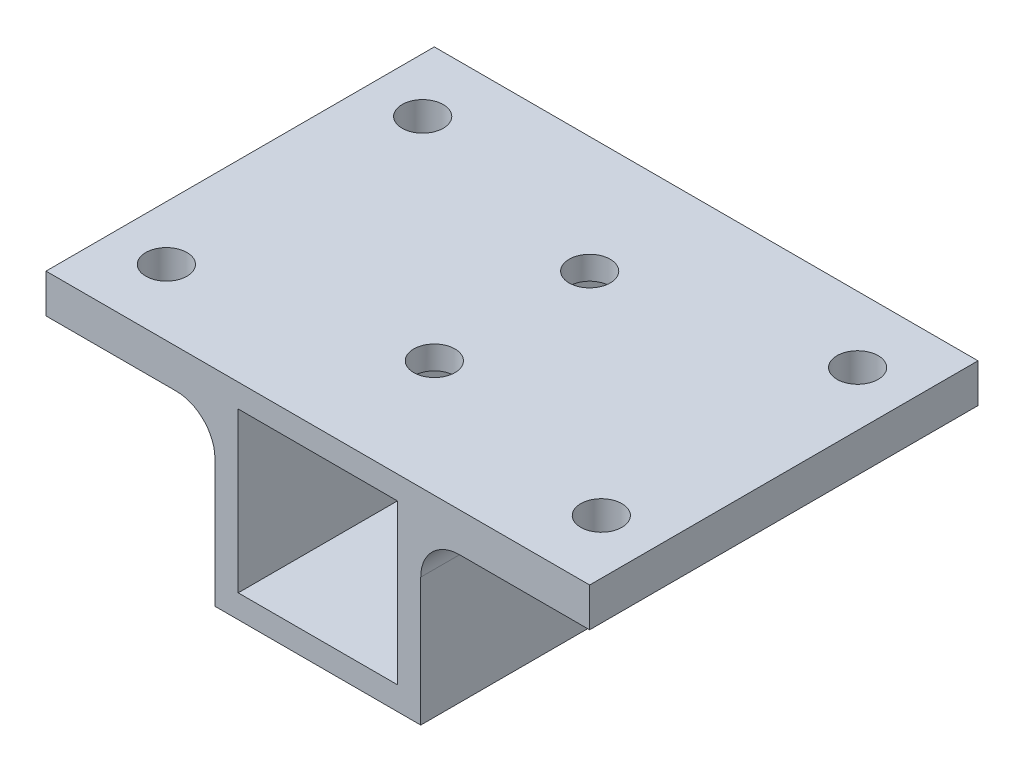
SolidWorks part; units mm, degrees
ref_plane "前视基准面" through (0, 0, 0) normal (0, 0, 1) x (1, 0, 0)
ref_plane "上视基准面" through (0, 0, 0) normal (0, 1, 0) x (1, 0, 0)
ref_plane "右视基准面" through (0, 0, 0) normal (1, 0, 0) x (0, 0, -1)
other "Configuration Table"
sketch "草图1" plane through (0, 0, 0) normal (0, 0, 1) x (1, 0, 0)
  line L0 (-13.25, 13.25) -> (13.25, 13.25)
  line L1 (-10.25, -10.25) -> (10.25, -10.25)
  line L2 (-10.25, -10.25) -> (-10.25, 10.25)
  line L3 (-10.25, 10.25) -> (10.25, 10.25)
  line L4 (10.25, -10.25) -> (10.25, 10.25)
  line L5 (-10.25, -10.25) -> (10.25, 10.25) construction
  line L6 (-10.25, 10.25) -> (10.25, -10.25) construction
  line L7 (13.25, -13.25) -> (13.25, 13.25)
  line L8 (-13.25, -13.25) -> (13.25, -13.25)
  line L9 (-13.25, -13.25) -> (-13.25, 13.25)
  point P0 (0, 0)
  dimension "D1" = 20.5
  dimension "D2" = 20.5
  dimension "D3" = 3
extrude "凸台-拉伸3" add sketch "草图1" along normal blind 50
sketch "草图2" plane through (0, 13.25, 0) normal (0, 1, 0) x (1, 0, 0)
  line L0 (-1013.25, -25) -> (48986.75, -25) construction
  line L1 (-13.25, -50) -> (-13.25, 0) construction
  line L2 (0, -1000) -> (0, 49000) construction
  line L3 (0, -25) -> (-28, -25)
  line L4 (-35, -50) -> (35, -50)
  line L5 (-35, -50) -> (-35, 0)
  line L6 (-35, 0) -> (35, 0)
  line L7 (35, -50) -> (35, 0)
  line L8 (-35, -50) -> (35, 0) construction
  line L9 (-35, 0) -> (35, -50) construction
  line L10 (-28, -25) -> (-28, -8.5)
  line L11 (-13.25, 0) -> (-13.25, -50)
  line L12 (13.25, 0) -> (13.25, -50)
  circle A0 centre (-28, -8.5) radius 2.65
  circle A1 centre (28, -8.5) radius 2.65
  circle A2 centre (28, -41.5) radius 2.65
  circle A3 centre (-28, -41.5) radius 2.65
  point P5 (-13.25, -25)
  point P6 (0, -25)
  dimension "D5" = 5.3
  dimension "D1" = 50
  dimension "D2" = 70
  dimension "D3" = 28
  dimension "D4" = 16.5
extrude "凸台-拉伸4" add sketch "草图2" against normal blind 5
sketch "草图3" plane through (0, 13.25, 0) normal (0, 1, 0) x (1, 0, 0)
  line L0 (0, 0) -> (0, -50)
  line L1 (35, -50) -> (-35, -50) construction
  line L2 (35, 0) -> (-35, 0) construction
  circle A0 centre (0, -35) radius 2.65
  circle A1 centre (0, -15) radius 2.65
  dimension "D1" = 15
  dimension "D2" = 5.3
  dimension "D3" = 5.3
  dimension "D4" = 15
extrude "切除-拉伸1" cut sketch "草图3" against normal through all contours L0 A1 | L0 A1 | L0 A0 | L0 A0
sketch "草图4" plane through (-13.25, 0, 0) normal (-1, 0, 0) x (0, 0, 1)
  line L0 (0, 0) -> (15, 0)
  line L1 (15, 0) -> (35, 0)
  circle A0 centre (15, 0) radius 2.65
  circle A1 centre (35, 0) radius 2.65
  dimension "D2" = 5.3
  dimension "D4" = 5.3
  dimension "D1" = 15
  dimension "D3" = 20
extrude "切除-拉伸2" cut sketch "草图4" against normal through all contours A0 | A1
fillet "圆角1" radius 5 2 edges at (-13.25, 8.25, 25) (13.25, 8.25, 25)
